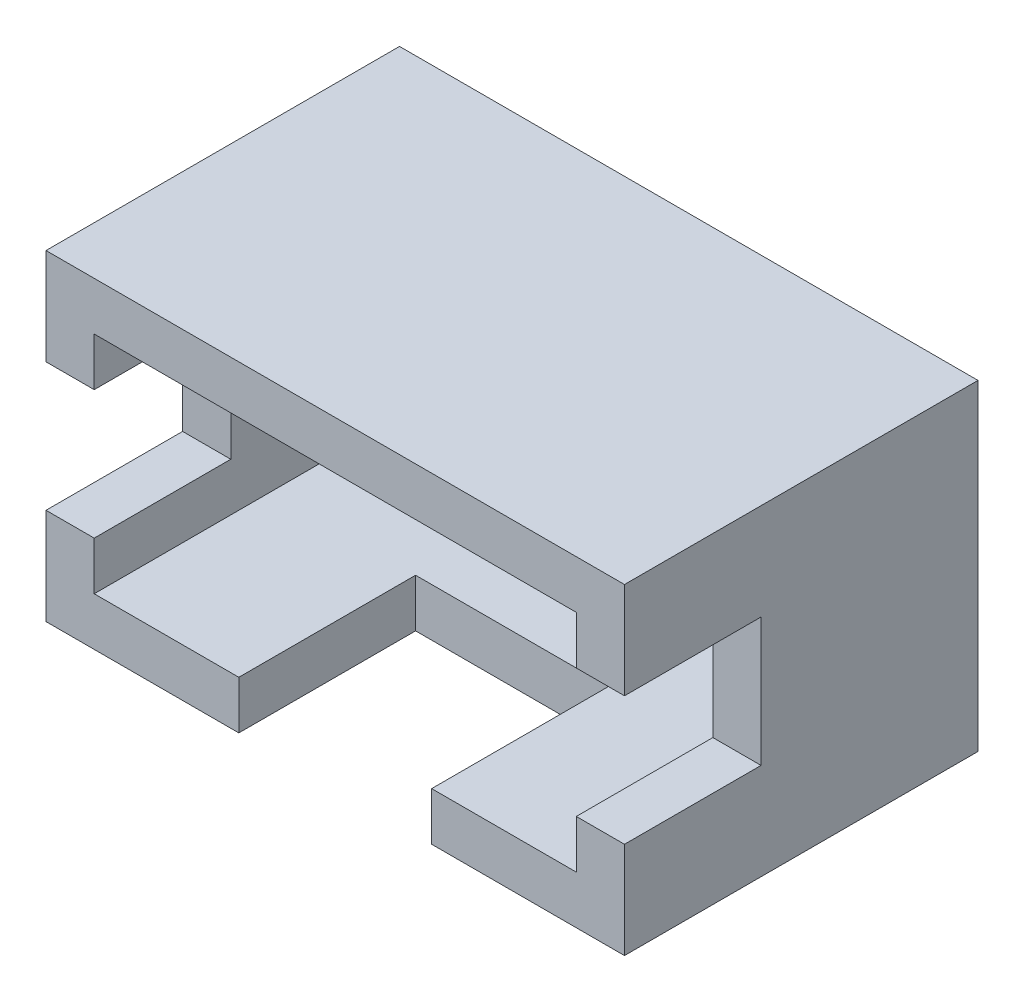
SolidWorks part; units mm, degrees
ref_plane "정면" through (0, 0, 0) normal (0, 0, 1) x (1, 0, 0)
ref_plane "윗면" through (0, 0, 0) normal (0, 1, 0) x (1, 0, 0)
ref_plane "우측면" through (0, 0, 0) normal (1, 0, 0) x (0, 0, -1)
sketch "스케치1" plane through (0, 0, 0) normal (0, 0, 1) x (1, 0, 0)
  line L0 (-3, -3) -> (33, -3)
  line L1 (0, 0) -> (30, 0)
  line L2 (0, 0) -> (0, 14)
  line L3 (0, 14) -> (30, 14)
  line L4 (30, 0) -> (30, 14)
  line L5 (33, -3) -> (33, 17)
  line L6 (-3, 17) -> (33, 17)
  line L7 (-3, -3) -> (-3, 17)
  dimension "D1" = 14
  dimension "D2" = 30
  dimension "D3" = 3
extrude "보스-돌출2" add sketch "스케치1" along normal blind 22 contours L1 L4 L3 L2 | L0 L5 L6 L7
sketch "스케치2" plane through (0, 0, 0) normal (0, 0, -1) x (-1, 0, 0)
  line L0 (0, 14) -> (-30, 14) construction
  line L1 (-20, 14) -> (-11, 14)
  line L2 (-20, 14) -> (-20, 0)
  line L3 (-20, 0) -> (-11, 0)
  line L4 (-11, 14) -> (-11, 0)
  line L5 (0, 0) -> (-30, 0) construction
  line L6 (0, 0) -> (0, 14) construction
  dimension "D1" = 11
  dimension "D2" = 20
extrude "보스-돌출3" add sketch "스케치2" against normal blind 4.5
sketch "스케치4" plane through (0, 0, 0) normal (0, 0, -1) x (-1, 0, 0)
  line L0 (3, -3) -> (-33, -3) construction
  line L1 (-14, -3) -> (-16, -3)
  line L2 (-14, -3) -> (-14, -5)
  line L3 (-14, -5) -> (-16, -5)
  line L4 (-16, -3) -> (-16, -5)
  point P6 (-15, -3)
  point P8 (-15, -3)
  dimension "D1" = 2
extrude "보스-돌출4" add sketch "스케치4" against normal blind 2
sketch "스케치5" plane through (0, -3, 0) normal (0, -1, 0) x (1, 0, 0)
  line L0 (-3, 22) -> (33, 22) construction
  line L1 (21, 22) -> (9, 22)
  line L2 (21, 22) -> (21, 11)
  line L3 (21, 11) -> (9, 11)
  line L4 (9, 22) -> (9, 11)
  point P8 (15, 22)
  dimension "D1" = 12
  dimension "D2" = 11
extrude "컷-돌출1" cut sketch "스케치5" against normal up to next
sketch "스케치6" plane through (0, 0, 22) normal (0, 0, 1) x (1, 0, 0)
  line L0 (-3, -3) -> (-3, 17) construction
  line L1 (-3, 3) -> (33, 3)
  line L2 (-3, 3) -> (-3, 11)
  line L3 (-3, 11) -> (33, 11)
  line L4 (33, 3) -> (33, 11)
  line L5 (33, -3) -> (33, 17) construction
  point P8 (-3, 7)
  point P10 (-3, 7)
  dimension "D1" = 8
extrude "컷-돌출2" cut sketch "스케치6" against normal blind 8.5
sketch "스케치7" plane through (0, 0, 0) normal (0, 0, -1) x (-1, 0, 0)
  line L1 (-33, -3) -> (-33, 17) construction
  point P6 (-33, 7)
